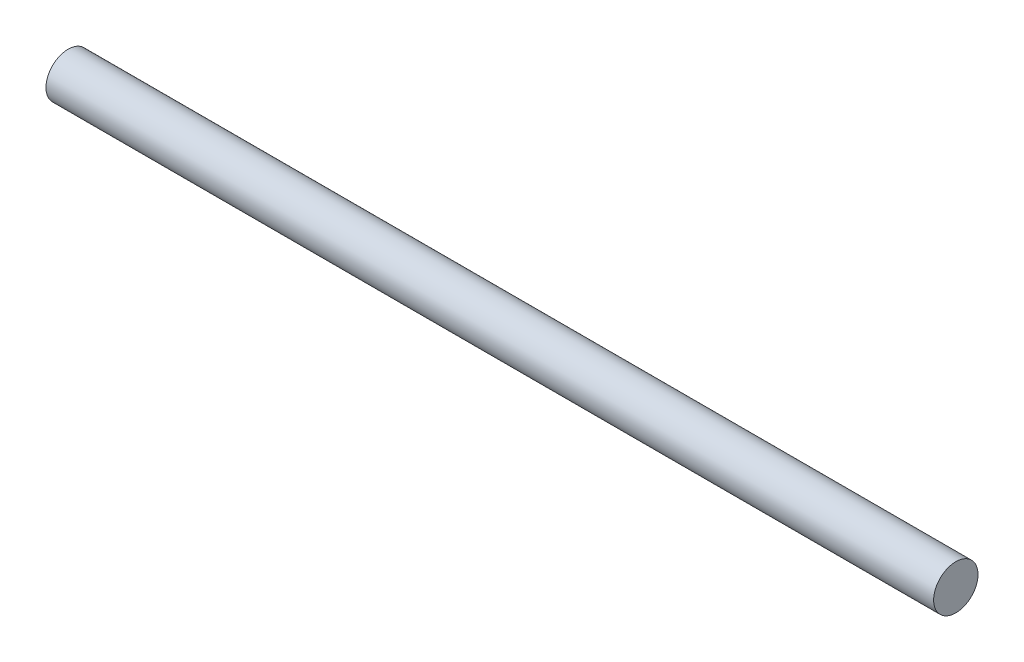
SolidWorks part; units mm, degrees
ref_plane "Plan de face" through (0, 0, 0) normal (0, 0, 1) x (1, 0, 0)
ref_plane "Plan de dessus" through (0, 0, 0) normal (0, 1, 0) x (1, 0, 0)
ref_plane "Plan de droite" through (0, 0, 0) normal (1, 0, 0) x (0, 0, -1)
sketch "Esquisse1" plane through (0, 0, 0) normal (1, 0, 0) x (0, 0, -1)
  circle A0 centre (0, 0) radius 1
  dimension "D1" = 2
extrude "Boss.-Extru.1" add sketch "Esquisse1" along normal blind 40
